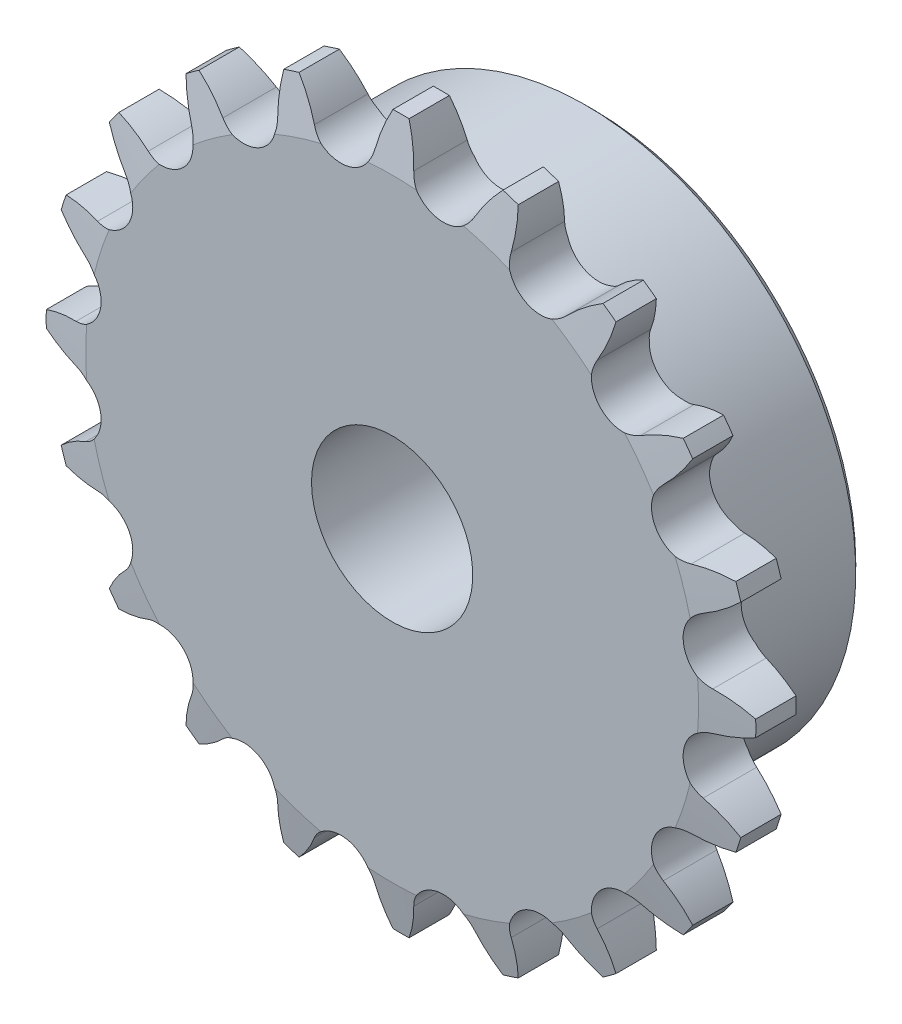
SolidWorks part; units mm, degrees
material "SUS304"
ref_plane "Front Plane" through (0, 0, 0) normal (0, 0, 1) x (1, 0, 0)
ref_plane "Top Plane" through (0, 0, 0) normal (0, 1, 0) x (1, 0, 0)
ref_plane "Right Plane" through (0, 0, 0) normal (1, 0, 0) x (0, 0, -1)
sketch "Sketch1" plane through (0, 0, 0) normal (1, 0, 0) x (0, 0, -1)
  line L0 (27.3653, 0) -> (0, 0) construction
  line L1 (0, 10) -> (25, 10)
  line L2 (25, 10) -> (25, 33.5)
  line L3 (25, 33.5) -> (7.2, 33.5)
  line L4 (7.2, 33.5) -> (7.2, 38)
  line L5 (6.1, 44) -> (1.1, 44)
  line L6 (0, 38) -> (0, 10)
  line L7 (6.1, 44) -> (7.2, 38)
  line L8 (3.6, 58.9526) -> (3.6, 63.7269) construction
  line L9 (1.1, 44) -> (0, 38)
  dimension "D1" = 7.2
  dimension "D2" = 5
  dimension "D3" = 20
  dimension "D4" = 88
  dimension "D5" = 6
  dimension "D6" = 67
  dimension "D7" = 25
revolve "Revolve1" add sketch "Sketch1" angle 360 about L0
chamfer "Chamfer1" distance 1 angle 45 1 edges at (-33.5, 0, -25)
sketch "Sketch2" plane through (0, 0, 0) normal (0, 0, 1) x (1, 0, 0)
  line L0 (0, 0) -> (0, 48.4341) construction
  line L1 (0, 0) -> (6.3497, 40.0903) construction
  circle A0 centre (0, 0) radius 40.59 construction
  circle A1 centre (-6.3497, 40.0903) radius 4 construction
  arc A2 (2.3961, 39.4826) -> (9.922, 38.2907) centre (6.3497, 40.0903) ccw
  circle A3 centre (18.4275, 36.166) radius 4 construction
  circle A4 centre (28.7015, 28.7015) radius 4 construction
  circle A5 centre (36.166, 18.4275) radius 4 construction
  circle A6 centre (40.0903, 6.3497) radius 4 construction
  circle A7 centre (40.0903, -6.3497) radius 4 construction
  circle A8 centre (36.166, -18.4275) radius 4 construction
  circle A9 centre (28.7015, -28.7015) radius 4 construction
  circle A10 centre (18.4275, -36.166) radius 4 construction
  circle A11 centre (6.3497, -40.0903) radius 4 construction
  circle A12 centre (-6.3497, -40.0903) radius 4 construction
  circle A13 centre (-18.4275, -36.166) radius 4 construction
  circle A14 centre (-28.7015, -28.7015) radius 4 construction
  circle A15 centre (-36.166, -18.4275) radius 4 construction
  circle A16 centre (-40.0903, -6.3497) radius 4 construction
  circle A17 centre (-40.0903, 6.3497) radius 4 construction
  circle A18 centre (-36.166, 18.4275) radius 4 construction
  circle A19 centre (-28.7015, 28.7015) radius 4 construction
  circle A20 centre (-18.4275, 36.166) radius 4 construction
  circle A21 centre (0, 0) radius 44 construction
  arc A22 (0, 44) -> (18.012, 40.1443) centre (0, 0) ccw construction
  arc A23 (1, 43.9886) -> (2.3961, 39.4826) centre (-13.4182, 37.0522) cw
  arc A24 (12.6422, 42.1447) -> (9.922, 38.2907) centre (24.2112, 31.0922) ccw
  arc A25 (12.6422, 42.1447) -> (1, 43.9886) centre (0, 0) ccw
  dimension "D1" = 81.18
  dimension "D2" = 20
  dimension "D3" = 8
  dimension "D5" = 16
  dimension "D4" = 2
extrude "Cut-Extrude1" cut sketch "Sketch2" against normal blind 10
pattern_circular "CirPattern1" count 20 over 360 about axis through (0, 0, 0) along (0, 0, 1) of "Cut-Extrude1"
equation "\"Mass Kg\"= \"SW-Mass\""
